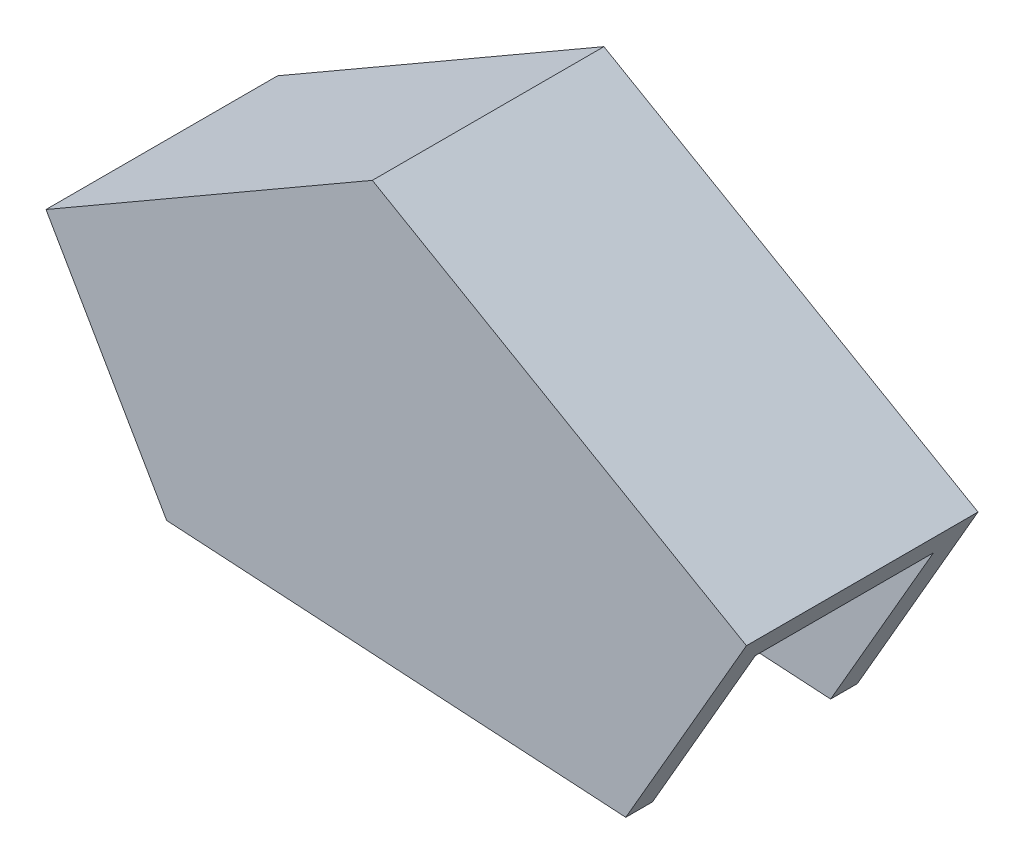
SolidWorks part; units mm, degrees
ref_plane "Front Plane" through (0, 0, 0) normal (0, 0, 1) x (1, 0, 0)
ref_plane "Top Plane" through (0, 0, 0) normal (0, 1, 0) x (1, 0, 0)
ref_plane "Right Plane" through (0, 0, 0) normal (1, 0, 0) x (0, 0, -1)
sketch "Sketch1" plane through (0, 0, 0) normal (0, 0, 1) x (1, 0, 0)
  line L0 (0, 0) -> (20, -11.547)
  line L1 (0, 0) -> (-17.3205, -10)
  line L2 (-9.7845, 0) -> (20.707, 0) construction
  line L3 (0, 2.3094) -> (21, -9.815)
  line L4 (0, 2.3094) -> (-18.3205, -8.2679)
  line L5 (-18.3205, -8.2679) -> (-17.3205, -10)
  line L6 (21, -9.815) -> (20, -11.547)
  dimension "D1" = 20
  dimension "D2" = 20
  dimension "D3" = 30
  dimension "D4" = 30
  dimension "D5" = 2
extrude "Boss-Extrude1" add sketch "Sketch1" along normal blind 10
sketch "Sketch2" plane through (0, 0, 10) normal (0, 0, 1) x (1, 0, 0)
  line L0 (-18.3205, -8.2679) -> (0, 2.3094)
  line L1 (0, 2.3094) -> (21, -9.815)
  line L2 (21, -9.815) -> (0, 2.3094) construction
  line L3 (21, -9.815) -> (20, -11.547)
  line L4 (20, -11.547) -> (14.2265, -21.547)
  line L5 (-18.3205, -8.2679) -> (-17.3205, -10)
  line L6 (-17.3205, -10) -> (-11.547, -20)
  line L7 (-11.547, -20) -> (14.2265, -21.547)
  dimension "D1" = 10
  dimension "D2" = 10
extrude "Boss-Extrude2" add sketch "Sketch2" along normal blind 1.5
ref_plane "Plane1" through (0, 0, 5) normal (0, 0, -1) x (-1, 0, 0)
mirror "Mirror1" about plane through (0, 0, 5) normal (0, 0, -1) of "Boss-Extrude2"
